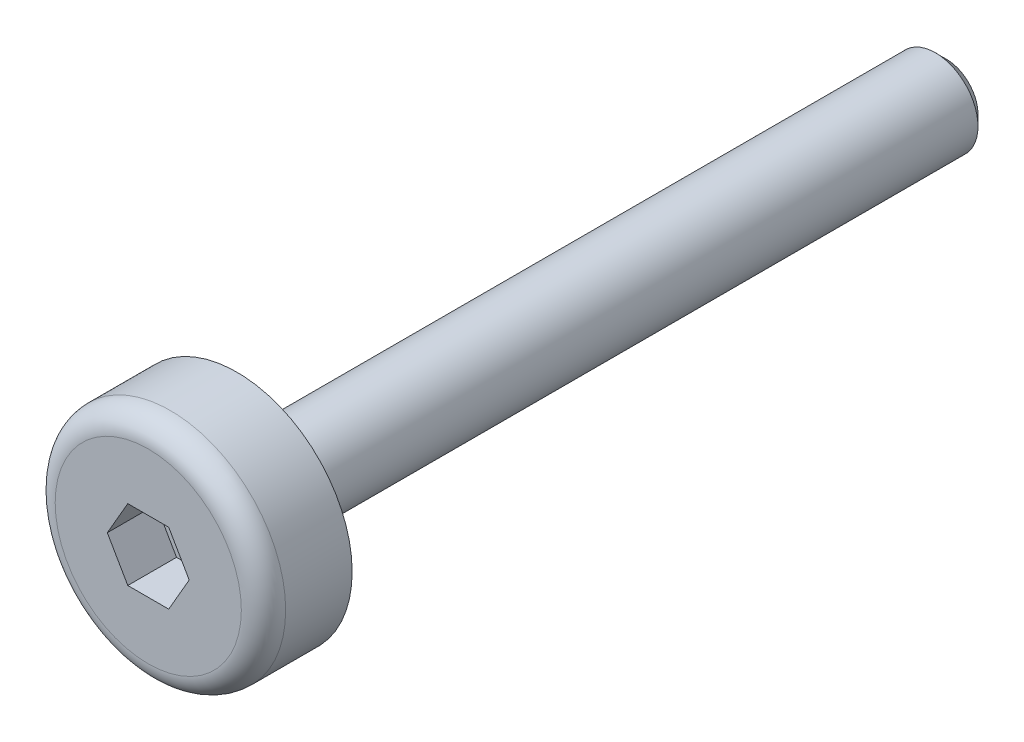
SolidWorks part; units mm, degrees
ref_plane "Front Plane" through (0, 0, 0) normal (0, 0, 1) x (1, 0, 0)
ref_plane "Top Plane" through (0, 0, 0) normal (0, 1, 0) x (1, 0, 0)
ref_plane "Right Plane" through (0, 0, 0) normal (1, 0, 0) x (0, 0, -1)
sketch "Screw Section" plane through (0, 0, 0) normal (0, 1, 0) x (1, 0, 0)
  line L0 (0, 20) -> (1.2, 20)
  line L1 (1.2, 20) -> (1.2, 0)
  line L2 (1.2, 0) -> (3.25, 0)
  line L3 (3.25, 0) -> (3.25, -2.5)
  line L4 (3.25, -2.5) -> (0, -2.5)
  line L5 (0, -2.5) -> (0, 20)
  line L6 (0, -10.123) -> (0, 10.123) construction
  dimension "D1" = 1.2
  dimension "D2" = 3.25
  dimension "D3" = 20
  dimension "D4" = 2.5
  dimension "D5" = 10.123
  dimension "D6" = 10.123
revolve "Screw Blank Revolve" add sketch "Screw Section" angle 360 about L6
chamfer "Shank Tip Chamfer" distance 0.3 1 edges at (1.2, 0, -20)
fillet "Pan Head Round" radius 0.625 1 edges at (3.25, 0, 2.5)
ref_plane "Head Crown Plane" through (0, 0, 2.5) normal (0, 0, 1) x (1, 0, 0)
sketch "Hex Drive Sketch" plane through (0, 0, 2.5) normal (0, 0, 1) x (1, 0, 0)
  line L1 (1.1547, 0) -> (0.5774, 1)
  line L2 (0.5774, 1) -> (-0.5774, 1)
  line L3 (-0.5774, 1) -> (-1.1547, 0)
  line L4 (-1.1547, 0) -> (-0.5774, -1)
  line L5 (-0.5774, -1) -> (0.5774, -1)
  line L6 (0.5774, -1) -> (1.1547, 0)
  circle A0 centre (0, 0) radius 1 construction
  dimension "D1" = 2
extrude "Hex Drive Cut" cut sketch "Hex Drive Sketch" against normal blind 1.375
equation "\"nominal_length\"= 20.0mm 'Screw length: under pan head or including flat head"
equation "\"model_shank_radius\"= 1.2mm 'Clearance envelope minor shank radius; thread is not modeled"
equation "\"head_diameter\"= 6.5mm 'Head outside diameter"
equation "\"head_height\"= 2.5mm 'Head axial height"
equation "\"drive_across_flats\"= 2mm 'Hex drive across flats"
equation "\"tip_chamfer\"= 0.3mm 'Shank tip chamfer"
equation "\"head_round\"= 0.625mm 'Pan head crown edge radius"
equation "\"drive_depth\"= 1.375mm 'Hex socket depth"
equation "\"axis_reference_halfspan\"= 10.123mm 'Half display length of the construction axis; avoids sharing a profile endpoint"
equation "\"D1@Screw Section\"= \"model_shank_radius\""
equation "\"D2@Screw Section\"= \"head_diameter\" / 2"
equation "\"D3@Screw Section\"= \"nominal_length\""
equation "\"D4@Screw Section\"= \"head_height\""
equation "\"D5@Screw Section\"= \"axis_reference_halfspan\""
equation "\"D6@Screw Section\"= \"axis_reference_halfspan\""
equation "\"full_turn\"= 360deg 'Full circular extent for revolves and patterns"
equation "\"D1@Screw Blank Revolve\"= \"full_turn\""
equation "\"D1@Shank Tip Chamfer\"= \"tip_chamfer\""
equation "\"D1@Pan Head Round\"= \"head_round\""
equation "\"D1@Head Crown Plane\"= \"head_height\""
equation "\"D1@Hex Drive Sketch\"= \"drive_across_flats\""
equation "\"D1@Hex Drive Cut\"= \"drive_depth\""
